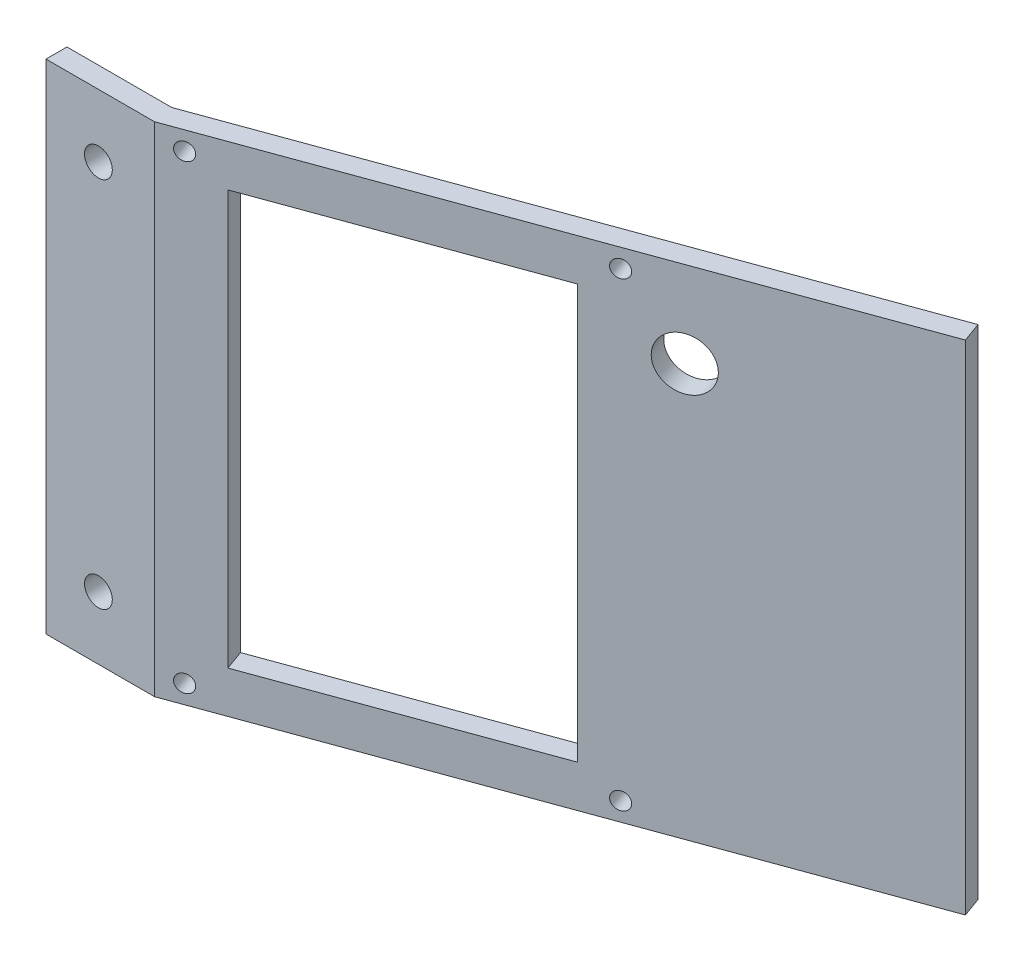
SolidWorks part; units mm, degrees
ref_plane "Front Plane" through (0, 0, 0) normal (1, 0, 0) x (0, 1, 0)
ref_plane "Top Plane" through (0, 0, 0) normal (0, 0, 1) x (0, 1, 0)
ref_plane "Right Plane" through (0, 0, 0) normal (0, 1, 0) x (-1, 0, 0)
sketch "Sketch1" plane through (0, 0, 0) normal (0, 0, 1) x (0, 1, 0)
  line L0 (-35.5, 0) -> (35.5, 0) construction
  line L1 (-47.5, 10) -> (47.5, 10)
  line L2 (-47.5, 10) -> (-47.5, -10)
  line L3 (-47.5, -10) -> (47.5, -10)
  line L4 (47.5, 10) -> (47.5, -10)
  line L5 (-47.5, 10) -> (47.5, -10) construction
  line L6 (-47.5, -10) -> (47.5, 10) construction
  circle A0 centre (35.5, 0) radius 2.65
  circle A1 centre (-35.5, 0) radius 2.65
  point P0 (0, 0)
  point P9 (0, 0)
  dimension "D2" = 5.3
  dimension "D1" = 20
  dimension "D3" = 12
  dimension "D4" = 95
extrude "Boss-Extrude1" add sketch "Sketch1" along normal blind 4
sketch "Sketch2" plane through (0, -47.5, 0) normal (0, -1, 0) x (1, 0, 0)
  line L0 (10, 0) -> (122.7631, -41.0424)
  line L1 (122.7631, -41.0424) -> (124.1312, -37.2836)
  line L2 (124.1312, -37.2836) -> (10.7053, 4)
  line L3 (10.7053, 4) -> (10, 4)
  line L4 (10, 4) -> (10, 0) construction
  line L5 (10, 4) -> (10, 0)
  line L6 (-10, 0) -> (10, 0) construction
  dimension "D1" = 160
  dimension "D2" = 120
extrude "Boss-Extrude2" add sketch "Sketch2" against normal up to surface (95 mm away) up to face at (0, 47.5, 2)
sketch "Sketch3" plane through (1.1698, 0, 3.2139) normal (-0.342, 0, -0.9397) x (0, -1, 0)
  line L0 (0, -13.1688) -> (0, -9.3969) construction
  line L1 (43.95, -13.1688) -> (-43.95, -13.1688) construction
  line L2 (43.95, -13.1688) -> (43.95, -78.0688) construction
  line L3 (43.95, -78.0688) -> (-43.95, -78.0688) construction
  line L4 (-43.95, -13.1688) -> (-43.95, -78.0688) construction
  line L5 (47.5, -9.3969) -> (-47.5, -9.3969) construction
  line L6 (-43.95, -45.6188) -> (-39.5, -45.6188) construction
  line L7 (39.5, -19.6188) -> (-39.5, -19.6188)
  line L8 (39.5, -19.6188) -> (39.5, -71.6188)
  line L9 (39.5, -71.6188) -> (-39.5, -71.6188)
  line L10 (-39.5, -19.6188) -> (-39.5, -71.6188)
  line L11 (0, -19.6188) -> (0, -13.1688) construction
  circle A0 centre (43.95, -13.1688) radius 1.65
  circle A1 centre (43.95, -78.0688) radius 1.65
  circle A2 centre (-43.95, -78.0688) radius 1.65
  circle A3 centre (-43.95, -13.1688) radius 1.65
  circle A5 centre (-31.1, -87.6188) radius 5
  dimension "D2" = 3.3
  dimension "D8" = 10
  dimension "D1" = 64.9
  dimension "D3" = 87.9
  dimension "D4" = 79
  dimension "D5" = 52
  dimension "D6" = 42
  dimension "D7" = 31.1
extrude "Cut-Extrude1" cut sketch "Sketch3" against normal through all
